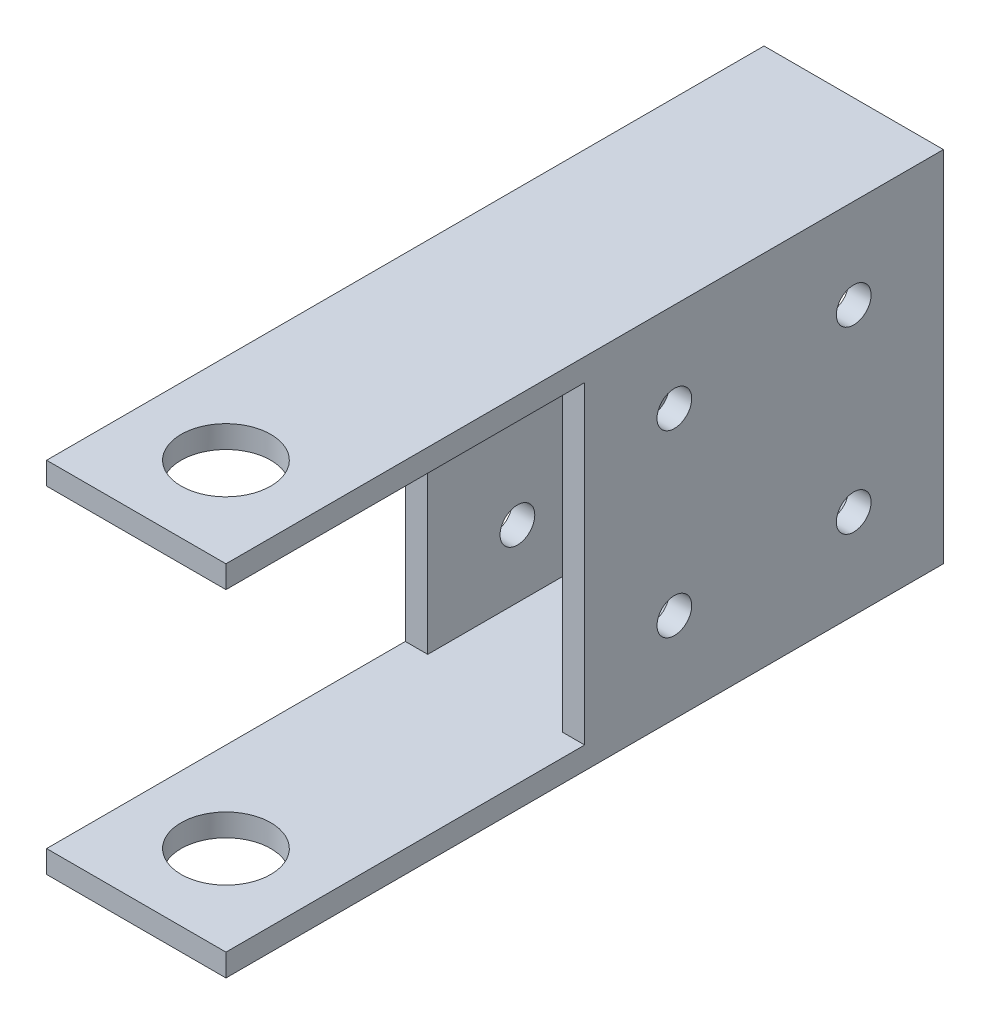
SolidWorks part; units mm, degrees
ref_plane "Front Plane" through (0, 0, 0) normal (0, 0, 1) x (1, 0, 0)
ref_plane "Top Plane" through (0, 0, 0) normal (0, 1, 0) x (1, 0, 0)
ref_plane "Right Plane" through (0, 0, 0) normal (1, 0, 0) x (0, 0, -1)
sketch "Sketch2" plane through (0, 0, 0) normal (0, 0, 1) x (1, 0, 0)
  line L1 (-12.7, 25.4) -> (12.7, 25.4)
  line L2 (-12.7, 25.4) -> (-12.7, -25.4)
  line L3 (-12.7, -25.4) -> (12.7, -25.4)
  line L4 (12.7, 25.4) -> (12.7, -25.4)
  line L5 (-12.7, 25.4) -> (12.7, -25.4) construction
  line L6 (-12.7, -25.4) -> (12.7, 25.4) construction
  point P0 (0, 0)
  dimension "D1" = 50.8
  dimension "D2" = 25.4
extrude "Boss-Extrude1" add sketch "Sketch2" along normal mid plane 101.6
sketch "Sketch3" plane through (12.7, 0, 0) normal (1, 0, 0) x (0, 0, -1)
  line L0 (0, 0) -> (-50.8, 0) construction
  line L1 (-50.8, -25.4) -> (-50.8, 25.4) construction
  line L2 (0, 22.225) -> (-50.8, 22.225)
  line L3 (0, -22.225) -> (-50.8, -22.225)
  line L4 (0, -22.225) -> (0, 22.225)
  line L5 (-50.8, -22.225) -> (-50.8, 22.225)
  dimension "D1" = 22.225
  dimension "D2" = 22.225
extrude "Cut-Extrude1" cut sketch "Sketch3" against normal through all
sketch "Sketch4" plane through (0, 25.4, 0) normal (0, 1, 0) x (1, 0, 0)
  line L0 (12.7, -50.8) -> (-12.7, -50.8) construction
  circle A0 centre (0, -38.1) radius 6.35
  dimension "D2" = 12.7
  dimension "D1" = 12.7
extrude "Cut-Extrude2" cut sketch "Sketch4" against normal through all
hole_wizard "#10 (0.1935) Diameter Hole2" positions "Sketch8" profile "Sketch7" hole size "#10" standard "ANSI Inch" end condition through all
sketch "Sketch8" plane through (12.7, 0, 0) normal (1, 0, 0) x (0, 0, -1)
  line L0 (12.7, 12.7) -> (38.1, 12.7) construction
  line L2 (0, 0) -> (50.8, 0) construction
  line L3 (50.8, -25.4) -> (50.8, 25.4) construction
  line L5 (-50.8, 25.4) -> (50.8, 25.4) construction
  point P0 (12.7, 12.7)
  point P2 (38.1, 12.7)
  point P4 (12.7, -12.7)
  point P6 (38.1, -12.7)
  dimension "D1" = 25.4
  dimension "D2" = 25.4
  dimension "D3" = 12.7
  dimension "D4" = 12.7
sketch "Sketch7" plane through (12.7, 12.7, -12.7) normal (0, 1, 0) x (0, 0, -1)
  line L0 (0, 0) -> (0, 25.4)
  line L1 (0, 25.4) -> (2.4574, 25.4)
  line L2 (2.4574, 25.4) -> (2.4574, 0)
  line L5 (2.4574, 0) -> (0, 0)
  line L11 (0, -6.35) -> (0, 107.95) construction
  dimension "Thru Hole Dia." = 4.9149
  dimension "Thru Hole Depth" = 25.4
sketch "Sketch9" plane through (0, 0, -50.8) normal (0, 0, -1) x (-1, 0, 0)
  line L8 (-9.525, 22.225) -> (-9.525, -22.225)
  line L9 (-9.525, -22.225) -> (9.525, -22.225)
  line L10 (9.525, -22.225) -> (9.525, 22.225)
  line L11 (9.525, 22.225) -> (-9.525, 22.225)
  line L12 (-9.525, 22.225) -> (-9.525, -22.225)
  line L13 (-9.525, -22.225) -> (9.525, -22.225)
  line L14 (9.525, -22.225) -> (9.525, 22.225)
  line L15 (9.525, 22.225) -> (-9.525, 22.225)
  dimension "D1" = 3.175
extrude "Cut-Extrude3" cut sketch "Sketch9" against normal through all
